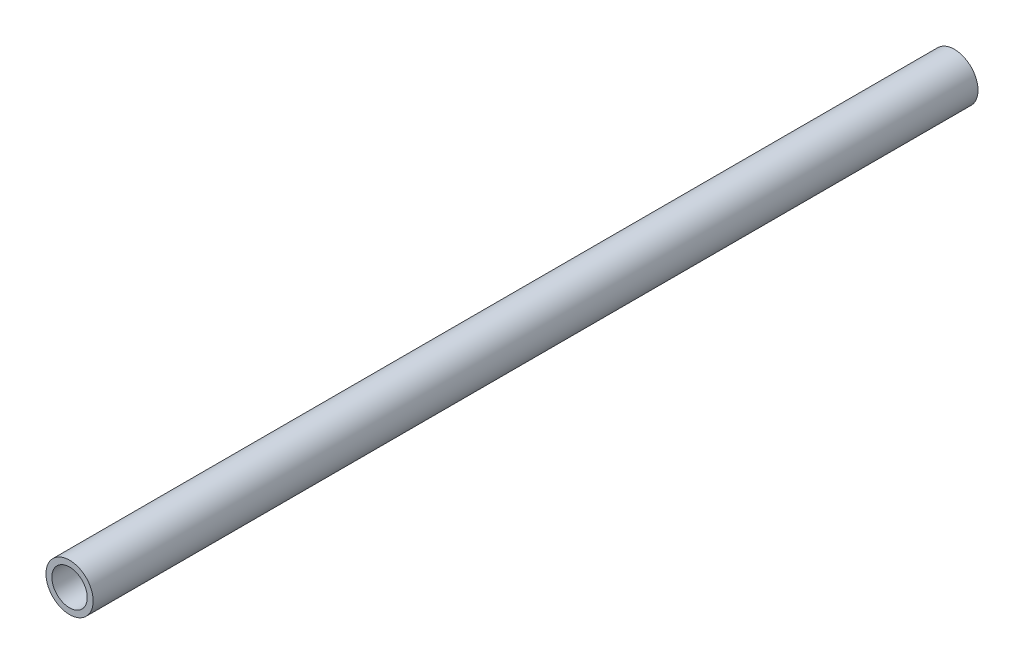
SolidWorks part; units mm, degrees
material "Thornel Mat VMA"
ref_plane "Front Plane" through (0, 0, 0) normal (0, 0, 1) x (1, 0, 0)
ref_plane "Top Plane" through (0, 0, 0) normal (0, 1, 0) x (1, 0, 0)
ref_plane "Right Plane" through (0, 0, 0) normal (1, 0, 0) x (0, 0, -1)
sketch "Sketch1" plane through (0, 0, 0) normal (0, 0, 1) x (1, 0, 0)
  circle A0 centre (0, 0) radius 4
  circle A1 centre (0, 0) radius 3
  dimension "D1" = 8
  dimension "D2" = 6
extrude "Boss-Extrude1" add sketch "Sketch1" along normal blind 150
